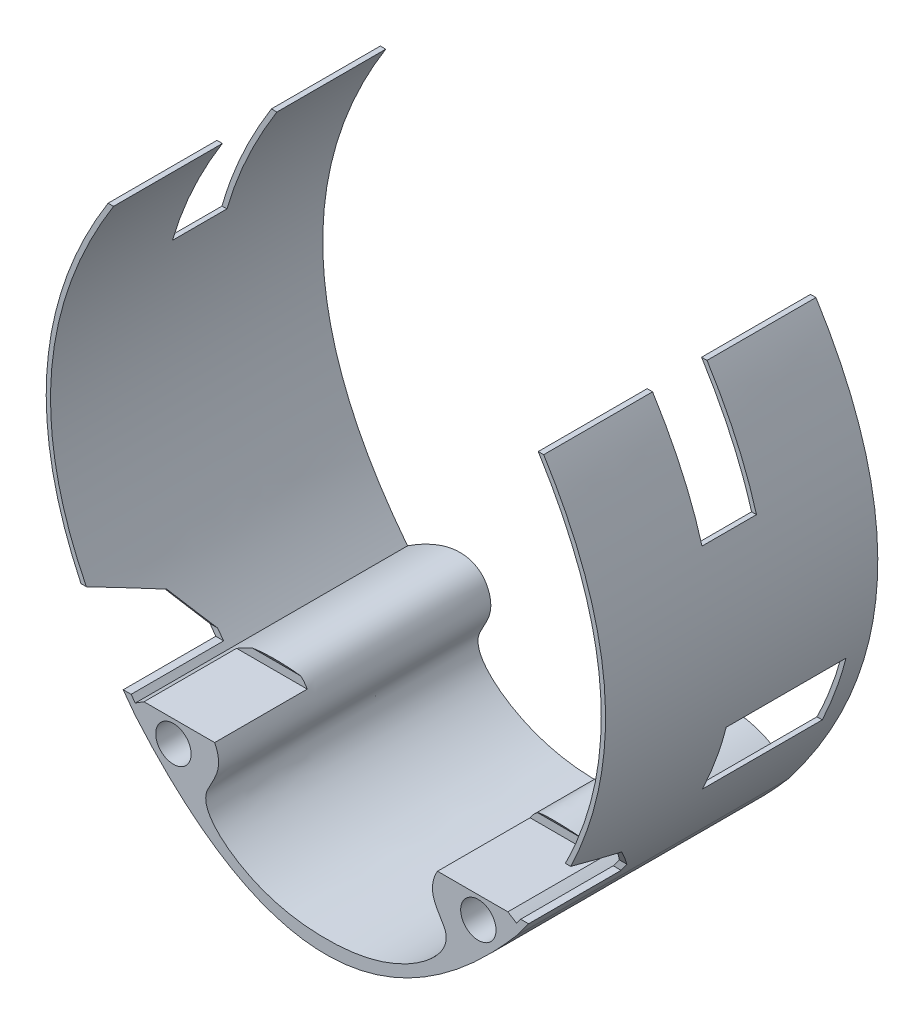
SolidWorks part; units mm, degrees
material "Balsa"
ref_plane "Front Plane" through (0, 0, 0) normal (0, 0, 1) x (1, 0, 0)
ref_plane "Top Plane" through (0, 0, 0) normal (0, 1, 0) x (1, 0, 0)
ref_plane "Right Plane" through (0, 0, 0) normal (1, 0, 0) x (0, 0, -1)
sketch "草圖1" plane through (0, 0, 0) normal (0, 0, 1) x (1, 0, 0)
  line L0 (0, 0) -> (-23.551, 0) construction
  line L1 (-35, 1) -> (0, -40) construction
  line L2 (0, -40) -> (35, 1) construction
  line L3 (-35, 1) -> (-65, 40) construction
  line L4 (-65, 40) -> (-40, 80) construction
  line L5 (35, 1) -> (65, 40) construction
  line L6 (65, 40) -> (40, 80) construction
  line L7 (-35, 3) -> (-64, 40) construction
  line L8 (-64, 40) -> (-39, 80) construction
  line L9 (35, 3) -> (64, 40) construction
  line L10 (64, 40) -> (39, 80) construction
  line L11 (-40, 80) -> (-39, 80)
  line L12 (39, 80) -> (40, 80)
  circle A0 centre (-28, 0) radius 3.25
  circle A1 centre (28, 0) radius 3.25
  circle A2 centre (0, 80) radius 3.25 construction
  spline S0 degree 2 poles (-35, 1) (0, -40) (35, 1) knots 0 0 0 1 1 1
  spline S1 degree 3 poles (-35, 3) (-23.9127, 10.2993) (-16.8625, 0.8713) (-25.2122, -5.9579) (-14.4761, -15.312) (0.0184, -17.8268) (14.4017, -15.3461) (25.4357, -5.8403) (16.5044, 0.4903) (24.2922, 10.1669) (35, 3) knots 0 0 0 0 0.105196 0.200517 0.353332 0.503002 0.652672 0.805487 0.900808 1 1 1 1
  spline S2 degree 2 poles (-35, 1) (-65, 40) (-40, 80) knots 0 0 0 1 1 1
  spline S3 degree 2 poles (35, 1) (65, 40) (40, 80) knots 0 0 0 1 1 1
  spline S4 degree 2 poles (-35, 3) (-64, 40) (-39, 80) knots 0 0 0 1 1 1
  spline S5 degree 2 poles (35, 3) (64, 40) (39, 80) knots 0 0 0 1 1 1
  dimension "D1" = 6.5
  dimension "D12" = 17
  dimension "D2" = 28
  dimension "D3" = 28
  dimension "D4" = 35
  dimension "D5" = 35
  dimension "D6" = 40
  dimension "D7" = 20
  dimension "D8" = 22
  dimension "D9" = 5
  dimension "D10" = 14
  dimension "D11" = 14
  dimension "D13" = 14
  dimension "D14" = 22
  dimension "D15" = 20
  dimension "D16" = 35
  dimension "D17" = 35
  dimension "D18" = 3
  dimension "D19" = 80
  dimension "D20" = 40
  dimension "D21" = 80
  dimension "D22" = 40
  dimension "D23" = 65
  dimension "D24" = 65
  dimension "D25" = 40
  dimension "D26" = 1
  dimension "D27" = 1
  dimension "D28" = 1
  dimension "D29" = 1
  dimension "D30" = 1
  dimension "D31" = 3
extrude "填料-伸長1" add sketch "草圖1" along normal blind 50
sketch "草圖2" plane through (0, 0, 0) normal (1, 0, 0) x (0, 0, -1)
  line L0 (-50, 80) -> (-50, 1) construction
  line L1 (-133, 13.5) -> (-50, 13.5)
  line L2 (-133, 13.5) -> (-133, 0.5)
  line L3 (-133, 0.5) -> (-56.7452, 0.5)
  line L4 (-33, 5.5) -> (-33, 4)
  line L5 (-50, -19.5) -> (0, -19.5) construction
  line L6 (-38, 12) -> (-50, 17)
  line L7 (-50, 80) -> (-50, 1) construction
  line L8 (-50, 17) -> (-50, 13.5)
  line L10 (-38, 12) -> (-33, 5.5)
  line L12 (-33, 4) -> (-50, 4)
  line L14 (-50, 4) -> (-56.7452, 0.5)
  line L15 (-50, 1) -> (0, 1) construction
  dimension "D1" = 17
  dimension "D2" = 13
  dimension "D3" = 20
  dimension "D4" = 3.5
  dimension "D5" = 3
  dimension "D6" = 5
  dimension "D7" = 11.5
  dimension "D8" = 5
extrude "除料-伸長2" cut sketch "草圖2" against normal through all and the other way through all
sketch "草圖3" plane through (0, 0, 0) normal (1, 0, 0) x (0, 0, -1)
  line L0 (-50, 80) -> (0, 80) construction
  line L1 (-30, 80) -> (-20, 80)
  line L2 (-30, 80) -> (-30, 60)
  line L3 (-30, 60) -> (-20, 60)
  line L4 (-20, 80) -> (-20, 60)
  line L5 (-50, 80) -> (-50, 17) construction
  line L6 (0, 1) -> (0, 80) construction
  dimension "D1" = 20
  dimension "D2" = 20
  dimension "D3" = 20
  dimension "D4" = 10
extrude "除料-伸長3" cut sketch "草圖3" against normal through all and the other way through all
sketch "草圖4" plane through (0, 0, 0) normal (1, 0, 0) x (0, 0, -1)
  line L0 (0, 1) -> (0, 80) construction
  line L1 (-26, 29.4043) -> (-4, 29.4043)
  line L2 (-26, 29.4043) -> (-26, 17.4043)
  line L3 (-26, 17.4043) -> (-4, 17.4043)
  line L4 (-4, 29.4043) -> (-4, 17.4043)
  dimension "D1" = 22
  dimension "D2" = 12
  dimension "D3" = 4
extrude "除料-伸長4" cut sketch "草圖4" along normal through all
